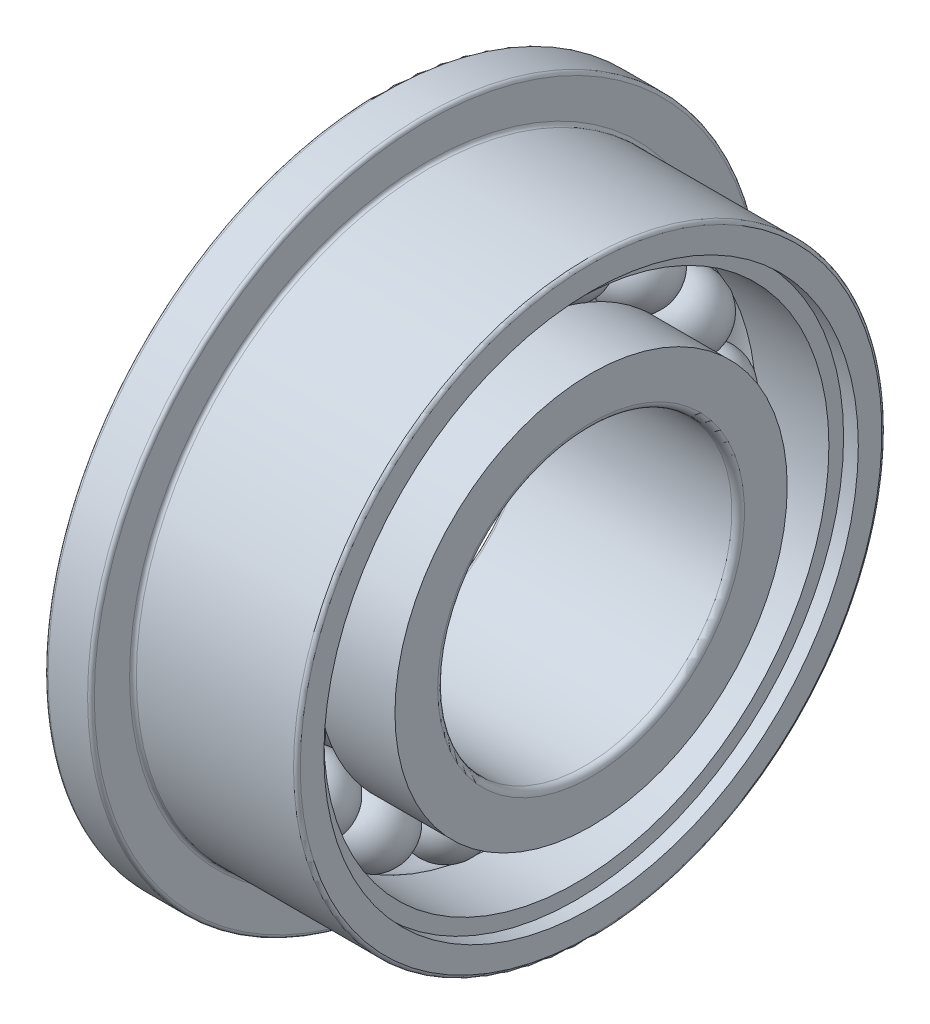
SolidWorks part; units mm, degrees
ref_plane "Front" through (0, 0, 0) normal (0, 0, 1) x (1, 0, 0)
ref_plane "Top" through (0, 0, 0) normal (0, 1, 0) x (1, 0, 0)
ref_plane "Right" through (0, 0, 0) normal (1, 0, 0) x (0, 0, -1)
sketch "Sketch1" plane through (0, 0, 0) normal (0, 0, 1) x (1, 0, 0)
  line L0 (-3.0919, 0) -> (2.899, 0) construction
  line L1 (-3.0919, 5.25) -> (2.899, 5.25) construction
  line L2 (-0.875, 5.25) -> (0.875, 5.25)
  arc A0 (-0.875, 5.25) -> (0.875, 5.25) centre (0, 5.25) ccw
  dimension "R" = 0.875
  dimension "D1" = 5.25
revolve "Revolve1" add sketch "Sketch1" angle 360 about L1
sketch "Sketch2" plane through (0, 0, 0) normal (0, 0, 1) x (1, 0, 0)
  line L0 (-2.5, 4.6667) -> (-0.6387, 4.6667)
  line L1 (2.5, 4.6667) -> (2.5, 3.5)
  line L2 (2.5, 3.5) -> (-2.5, 3.5)
  line L3 (-2.5, 3.5) -> (-2.5, 4.6667)
  line L4 (-2.9924, 0) -> (3.9982, 0) construction
  line L5 (-1.8743, 5.25) -> (3.1755, 5.25) construction
  line L7 (0.6387, 4.6667) -> (2.5, 4.6667)
  line L8 (-2.5, 6.2861) -> (-2.5, 1.454) construction
  arc A0 (-0.6387, 4.6667) -> (0.6387, 4.6667) centre (0, 5.25) ccw
  dimension "D1" = 5.25
  dimension "B" = 5
  dimension "D2" = 0.865
  dimension "d" = 7
  dimension "D3" = 9.3333
  dimension "T" = 5
  dimension "D6" = 2.5
revolve "Revolve2" add sketch "Sketch2" angle 360 about L4
sketch "Sketch3" plane through (0, 0, 0) normal (0, 0, 1) x (1, 0, 0)
  line L0 (-2.5, 5.8333) -> (-2.5, 7)
  line L1 (-2.5, 7) -> (2.5, 7)
  line L2 (2.5, 7) -> (2.5, 6.3583)
  line L3 (2.15, 6.0083) -> (0.4161, 6.0083)
  line L4 (-2.9924, 0) -> (3.4329, 0) construction
  line L6 (-1.7375, 5.25) -> (2.2712, 5.25) construction
  line L7 (-0.6387, 5.8333) -> (-2.5, 5.8333)
  line L8 (2.15, 6.0083) -> (2.15, 6.3583)
  line L9 (2.15, 6.3583) -> (2.5, 6.3583)
  arc A0 (0.4161, 6.0083) -> (-0.6387, 5.8333) centre (0, 5.25) ccw
  dimension "D1" = 5.25
  dimension "D4" = 0.865
  dimension "B" = 5
  dimension "DD" = 14
  dimension "D3" = 12.0167
  dimension "D5" = 11.6667
  dimension "D6" = 0.35
  dimension "D7" = 0.35
  dimension "D2" = 2.5
revolve "Revolve3" add sketch "Sketch3" angle 360 about L4
pattern_circular "Circular-Pattern1" count 17 over 360 about axis through (0, 0, 0) along (1, 0, 0) of "Revolve1"
fillet "Fillet1" radius 0.15 1 edges at (2.5, 0, 3.5)
fillet "Fillet2" radius 0.08 2 edges at (2.5, 0, 7) (-2.5, 0, 3.5)
sketch "草图1" plane through (-2.5, 0, 0) normal (-1, 0, 0) x (0, 0, 1)
  circle A0 centre (0, 0) radius 8
  circle A1 centre (0, 0) radius 7
  circle A2 centre (0, 0) radius 7 construction
  dimension "D1" = 16
extrude "凸台-拉伸1" add sketch "草图1" against normal blind 1.1
fillet "圆角1" radius 0.08 3 edges at (-1.4, 0, 8) (-2.5, 0, 8) (-1.4, 0, 7)
equation "\"R@Sketch1\" =  ( \"DD@Sketch3\" - \"d@Sketch2\" )  / 8"
equation "\"D1@Sketch1\"=(\"d@Sketch2\"+\"DD@Sketch3\")/4"
equation "\"D1@Sketch2\"=(\"d@Sketch2\"+\"DD@Sketch3\")/4"
equation "\"D3@Sketch2\" =  \"d@Sketch2\"+  ( \"DD@Sketch3\" - \"d@Sketch2\" )  /3"
equation "\"D2@Sketch2\" =  ( \"DD@Sketch3\" - \"d@Sketch2\" )  / 8 - 0.01"
equation "\"D6@Sketch2\" = \"B@Sketch2\" / 2"
equation "\"B@Sketch3\" = \"B@Sketch2\""
equation "\"D2@Sketch3\" = \"B@Sketch3\" / 2"
equation "\"D1@Sketch3\"=(\"d@Sketch2\"+\"DD@Sketch3\")/4"
equation "\"D3@Sketch3\" = (  \"DD@Sketch3\" -  (\"DD@Sketch3\" - \"d@Sketch2\"  )  / 3 )  * 1.03"
equation "\"D5@Sketch3\" = \"DD@Sketch3\" -  (  \"DD@Sketch3\" - \"d@Sketch2\")  / 3"
equation "\"D6@Sketch3\" = \"d@Sketch2\" / 20"
equation "\"D7@Sketch3\"=\"D6@Sketch3\""
equation "\"D4@Sketch3\"=(\"DD@Sketch3\"-\"d@Sketch2\")/8-0.01"
equation "\"m@Circular-Pattern1\" = int( 3.14159265 / atn(\"R@Sketch1\" / sqr((\"d@Sketch2\"+\"DD@Sketch3\")/4 * (\"d@Sketch2\"+\"DD@Sketch3\")/4 - \"R@Sketch1\" *  \"R@Sketch1\")))-1"
